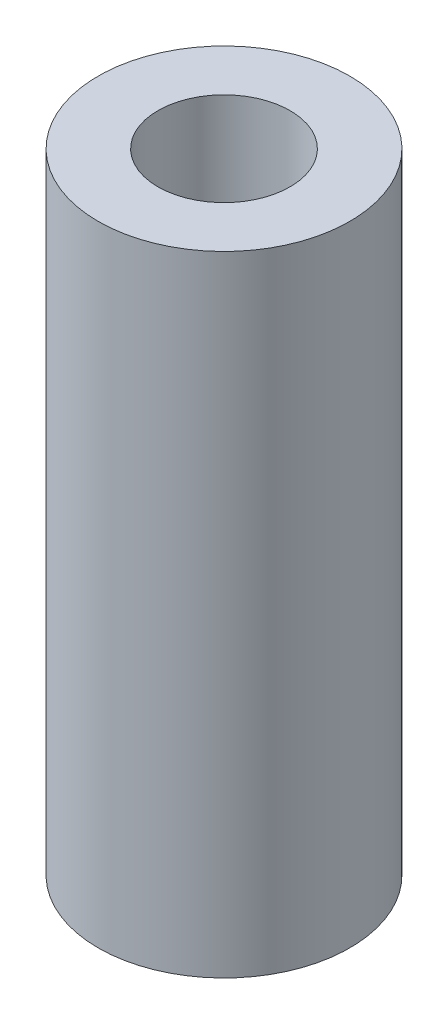
SolidWorks part; units mm, degrees
ref_plane "前视基准面" through (0, 0, 0) normal (0, 0, 1) x (1, 0, 0)
ref_plane "上视基准面" through (0, 0, 0) normal (0, 1, 0) x (1, 0, 0)
ref_plane "右视基准面" through (0, 0, 0) normal (1, 0, 0) x (0, 0, -1)
sketch "Sketch1" plane through (0, 0, 0) normal (0, 1, 0) x (1, 0, 0)
  circle A0 centre (0, 0) radius 2.1
  circle A1 centre (0, 0) radius 4
  dimension "D1" = 4.2
  dimension "D2" = 8
extrude "Boss-Extrude1" add sketch "Sketch1" along normal blind 20
